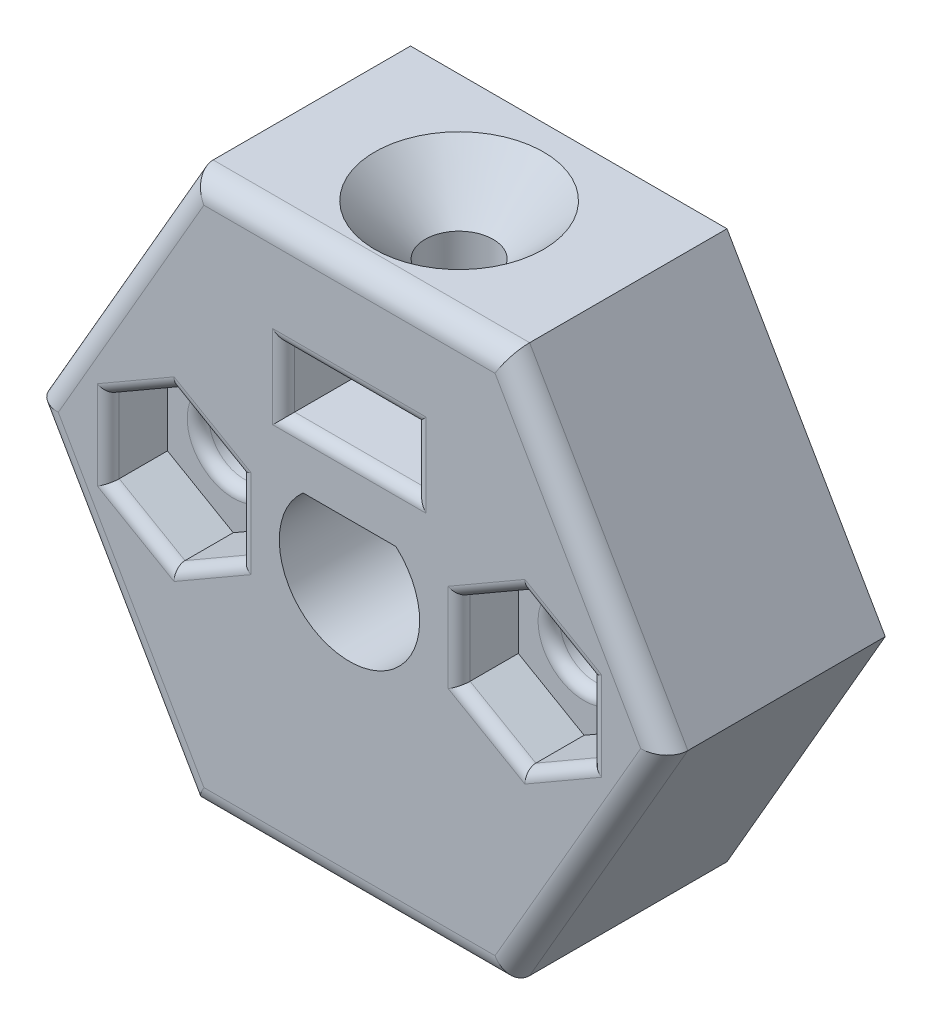
SolidWorks part; units mm, degrees
material "ABS"
ref_plane "Спереди" through (0, 0, 0) normal (0, 0, 1) x (1, 0, 0)
ref_plane "Сверху" through (0, 0, 0) normal (0, 1, 0) x (1, 0, 0)
ref_plane "Справа" through (0, 0, 0) normal (1, 0, 0) x (0, 0, -1)
sketch "Эскиз1" plane through (0, 0, 0) normal (0, 0, 1) x (1, 0, 0)
  line L1 (7.2169, -12.5) -> (14.4338, 0)
  line L2 (14.4338, 0) -> (7.2169, 12.5)
  line L3 (7.2169, 12.5) -> (-7.2169, 12.5)
  line L4 (-7.2169, 12.5) -> (-14.4338, 0)
  line L5 (-14.4338, 0) -> (-7.2169, -12.5)
  line L6 (-7.2169, -12.5) -> (7.2169, -12.5)
  circle A0 centre (0, 0) radius 12.5 construction
  dimension "D1" = 25
extrude "Бобышка-Вытянуть1" add sketch "Эскиз1" along normal blind 10
sketch "Эскиз2" plane through (0, 0, 10) normal (0, 0, 1) x (1, 0, 0)
  line L0 (-2.0396, 2.2) -> (2.0396, 2.2) construction
  line L1 (0, 2.2) -> (0, -3) construction
  line L2 (3, 0) -> (3.2, 0) construction
  line L3 (-2.1166, 2.4) -> (2.1166, 2.4)
  line L4 (0, 2.4) -> (0, 2.2) construction
  arc A0 (-2.0396, 2.2) -> (2.0396, 2.2) centre (0, 0) ccw construction
  arc A1 (-2.1166, 2.4) -> (2.1166, 2.4) centre (0, 0) ccw
  dimension "D1" = 6
  dimension "D2" = 5.2
  dimension "D3" = 0.2
extrude "Вырез-Вытянуть1" cut sketch "Эскиз2" against normal through all
sketch "Эскиз3" plane through (0, 2.4, 0) normal (0, -1, 0) x (1, 0, 0)
  line L0 (0, 5) -> (0, 0) construction
  line L3 (0, 5) -> (0, 10) construction
  line L4 (2.1166, 10) -> (-2.1166, 10) construction
  circle A0 centre (0, 5) radius 1.55
  dimension "D1" = 3.1
extrude "Вырез-Вытянуть2" cut sketch "Эскиз3" against normal up to surface (10.1 mm away) up to face at (0, 12.5, 5)
chamfer "Фаска1" distance 2.3 angle 45 1 edges at (1.55, 12.5, 5)
sketch "Эскиз4" plane through (0, 0, 10) normal (0, 0, 1) x (1, 0, 0)
  line L0 (0, 2.4) -> (0, 12.5) construction
  line L1 (2.1166, 2.4) -> (-2.1166, 2.4) construction
  line L2 (7.2169, 12.5) -> (-7.2169, 12.5) construction
  line L4 (-3, 7.7) -> (3, 7.7)
  line L5 (-3, 7.7) -> (-3, 4.9)
  line L6 (-3, 4.9) -> (3, 4.9)
  line L7 (3, 7.7) -> (3, 4.9)
  line L8 (-3, 7.7) -> (3, 4.9) construction
  line L9 (-3, 4.9) -> (3, 7.7) construction
  point P6 (0, 6.3)
  dimension "D1" = 6
  dimension "D2" = 2.8
  dimension "D3" = 2.5
extrude "Вырез-Вытянуть3" cut sketch "Эскиз4" against normal offset from surface (8.5 mm away) 1.5 up to face at (0, -0.4, 0)
fillet "Скругление1" radius 1 6 edges at (-10.8253, -6.25, 10) (0, -12.5, 10) (10.8253, -6.25, 10) (10.8253, 6.25, 10) (0, 12.5, 10) (-10.8253, 6.25, 10)
sketch "Эскиз5" plane through (0, 0, 10) normal (0, 0, 1) x (1, 0, 0)
  line L0 (0, 0) -> (-8, 0) construction
  line L1 (0, 0) -> (0, 4.9) construction
  line L2 (-11, -1.7321) -> (-8, -3.4641)
  line L3 (-8, -3.4641) -> (-5, -1.7321)
  line L4 (-5, -1.7321) -> (-5, 1.7321)
  line L5 (-5, 1.7321) -> (-8, 3.4641)
  line L6 (-8, 3.4641) -> (-11, 1.7321)
  line L7 (-11, 1.7321) -> (-11, -1.7321)
  line L8 (-3, 4.9) -> (3, 4.9) construction
  line L9 (8, -3.4641) -> (5, -1.7321)
  line L10 (11, -1.7321) -> (8, -3.4641)
  line L11 (11, 1.7321) -> (11, -1.7321)
  line L12 (8, 3.4641) -> (11, 1.7321)
  line L13 (5, 1.7321) -> (8, 3.4641)
  line L14 (5, -1.7321) -> (5, 1.7321)
  circle A0 centre (-8, 0) radius 3 construction
  dimension "D1" = 6
  dimension "D2" = 8
extrude "Вырез-Вытянуть4" cut sketch "Эскиз5" against normal blind 2.7
sketch "Эскиз6" plane through (0, 0, 7.3) normal (0, 0, 1) x (1, 0, 0)
  line L0 (-8, 0) -> (-5, 0) construction
  line L1 (-5, -1.7321) -> (-5, 1.7321) construction
  line L2 (-8, 0) -> (-11, 0) construction
  line L3 (-11, 1.7321) -> (-11, -1.7321) construction
  line L4 (0, 0) -> (0, 5.4418) construction
  circle A0 centre (-8, 0) radius 1.6
  circle A1 centre (8, 0) radius 1.6
  dimension "D1" = 3.2
extrude "Вырез-Вытянуть5" cut sketch "Эскиз6" against normal up to surface (7.3 mm away) up to face at (0, -0.4, 0)
fillet "Скругление2" radius 0.5 18 edges at (3, 6.3, 10) (0, 4.9, 10) (-3, 6.3, 10) (0, 7.7, 10) (-6.4, 0, 7.3) (6.4, 0, 7.3) (5, 0, 10) (6.5, -2.5981, 10) (9.5, -2.5981, 10) (11, 0, 10) (9.5, 2.5981, 10) (6.5, 2.5981, 10) (-9.5, -2.5981, 10) (-6.5, -2.5981, 10) (-5, 0, 10) (-6.5, 2.5981, 10) (-11, 0, 10) (-9.5, 2.5981, 10)
